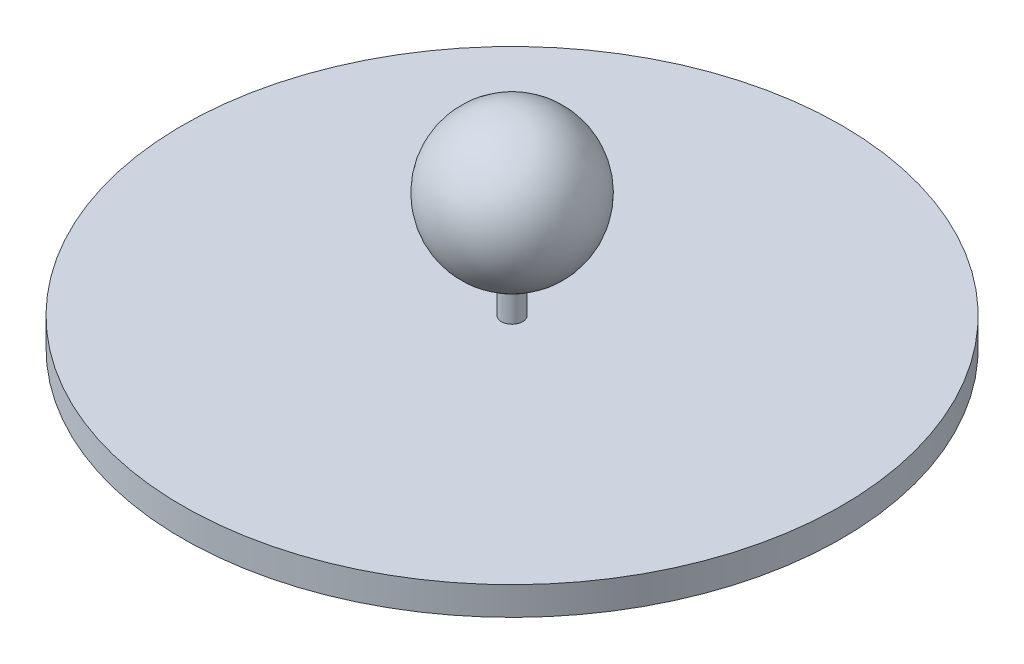
SolidWorks part; units mm, degrees
ref_plane "前视基准面" through (0, 0, 0) normal (0, 0, 1) x (1, 0, 0)
ref_plane "上视基准面" through (0, 0, 0) normal (0, 1, 0) x (1, 0, 0)
ref_plane "右视基准面" through (0, 0, 0) normal (1, 0, 0) x (0, 0, -1)
sketch "草图1" plane through (0, 0, 0) normal (0, 0, 1) x (1, 0, 0)
  line L0 (0, 0) -> (20, 0)
  line L1 (20, 0) -> (20, 100)
  line L2 (20, 100) -> (15, 100)
  line L3 (15, 100) -> (15, 200)
  line L4 (15, 200) -> (465, 200)
  line L5 (465, 200) -> (465, 240)
  line L6 (465, 240) -> (15, 240)
  line L7 (15, 240) -> (15, 290)
  line L8 (15, 290) -> (0, 290)
  line L9 (0, 290) -> (0, 0)
  line L10 (0, 290) -> (0, 390)
  line L11 (0, 390) -> (0, 491.1187)
  circle A0 centre (0, 390) radius 101.1187
  point P4 (0, 0)
revolve "旋转1" add sketch "草图1" angle 360 about L10
